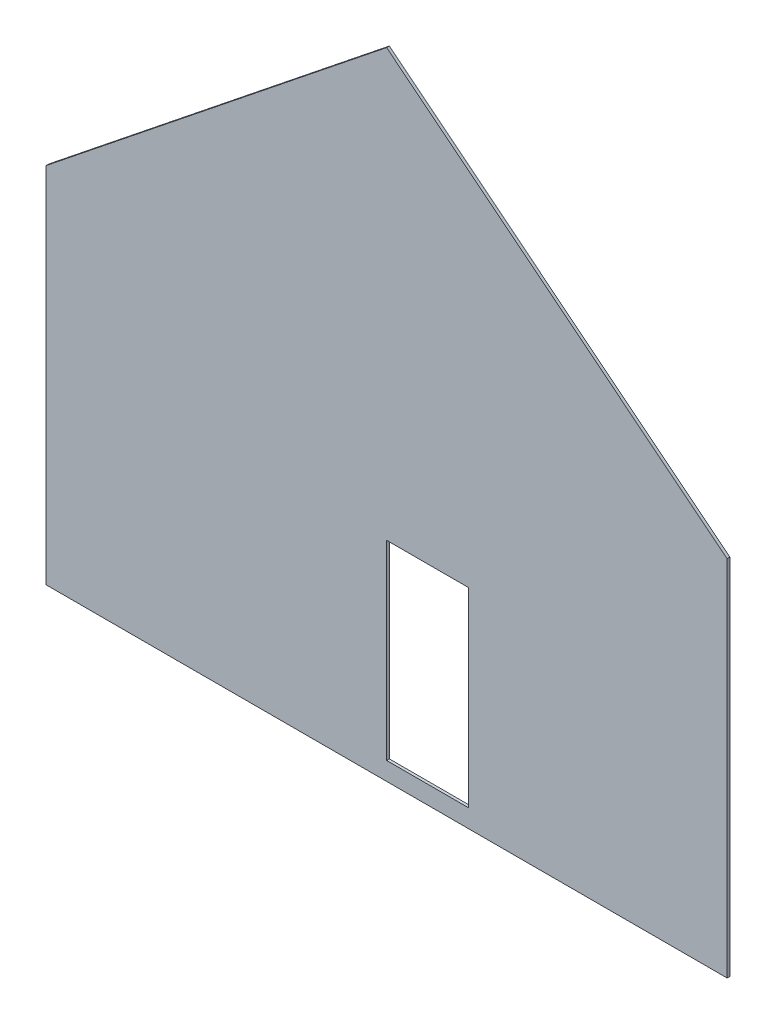
SolidWorks part; units mm, degrees
ref_plane "Front Plane" through (0, 0, 0) normal (0, 0, 1) x (1, 0, 0)
ref_plane "Top Plane" through (0, 0, 0) normal (0, 1, 0) x (1, 0, 0)
ref_plane "Right Plane" through (0, 0, 0) normal (1, 0, 0) x (0, 0, -1)
sketch "Sketch1" plane through (0, 0, 0) normal (0, 0, 1) x (1, 0, 0)
  line L0 (0, 0) -> (7500, 0)
  line L1 (3750, 0) -> (3750, 7000)
  line L2 (0, 0) -> (0, 4000)
  line L3 (7500, 0) -> (7500, 4000)
  line L4 (3750, 7000) -> (0, 4000)
  line L6 (3750, 7000) -> (7500, 4000)
  dimension "D1" = 7500
  dimension "D2" = 7000
  dimension "D3" = 4000
  dimension "D4" = 4000
extrude "Boss-Extrude1" add sketch "Sketch1" along normal blind 30 contours L6 L3 L0 L2 L4
sketch "Sketch2" plane through (0, 0, 30) normal (0, 0, 1) x (1, 0, 0)
  line L0 (0, 200) -> (7500, 200) construction
  line L1 (3750, 2300) -> (4650, 2300)
  line L2 (3750, 2300) -> (3750, 200)
  line L3 (3750, 200) -> (4650, 200)
  line L4 (4650, 2300) -> (4650, 200)
  line L5 (0, 200) -> (7500, 200)
  line L6 (0, 0) -> (0, 4000) construction
  dimension "D1" = 900
  dimension "D2" = 2100
  dimension "D3" = 3750
extrude "Cut-Extrude1" cut sketch "Sketch2" against normal blind 1353 contours L2 L1 L4 L3
